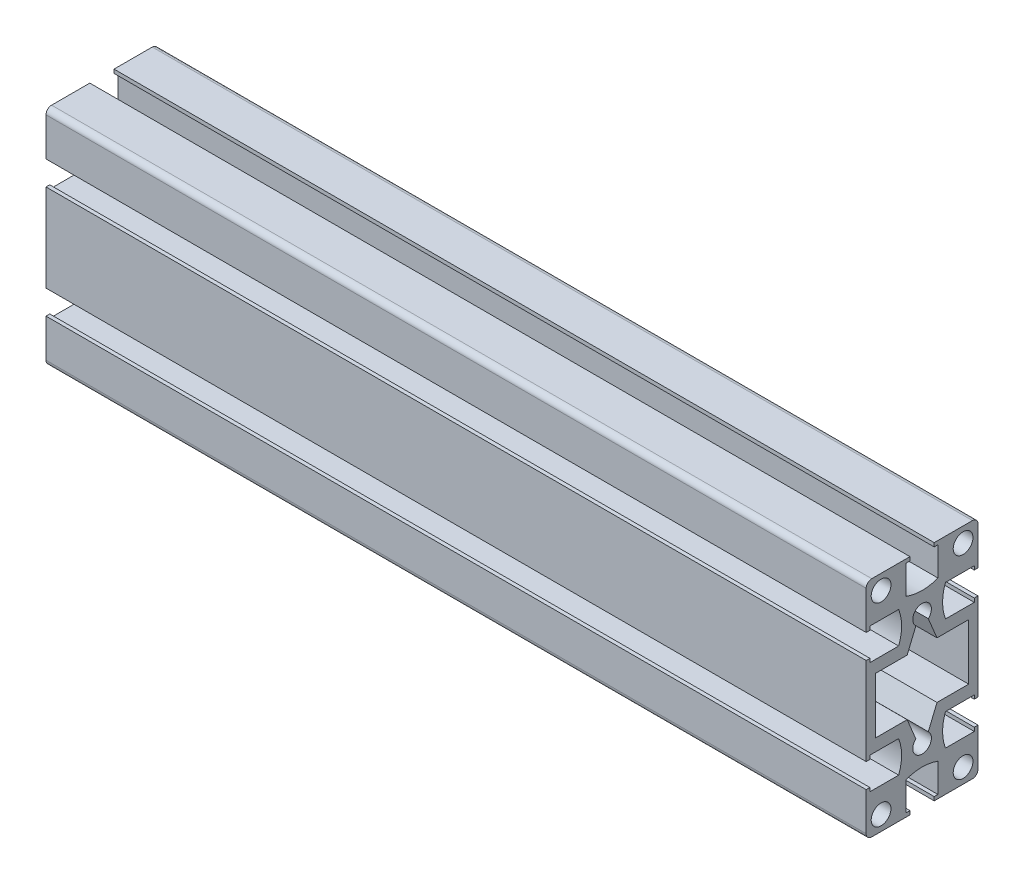
SolidWorks part; units mm, degrees
ref_plane "前视基准面" through (0, 0, 0) normal (0, 0, 1) x (1, 0, 0)
ref_plane "上视基准面" through (0, 0, 0) normal (0, 1, 0) x (1, 0, 0)
ref_plane "右视基准面" through (0, 0, 0) normal (1, 0, 0) x (0, 0, -1)
sketch "草图1" plane through (0, 0, 0) normal (0, 1, 0) x (1, 0, 0)
  line L0 (0, 0) -> (220, 0)
  dimension "D1" = 220
other "铝型材 30 X 60G X R1.5(1)"
ref_plane "基准面1" through (0, 0, 0) normal (1, 0, 0) x (0, 0, -1)
sketch "Sketch1" plane through (0, 0, 0) normal (1, 0, 0) x (0, 0, -1)
  line L0 (-3.25, 30) -> (-3.25, 29)
  line L1 (-13.5, 30) -> (-3.25, 30)
  line L2 (-15, 28.5) -> (-15, 18.25)
  line L3 (-13.5, -30) -> (-3.25, -30)
  line L4 (15, 28.5) -> (15, 18.25)
  line L5 (-12.5, 7.5) -> (-4, 7.5)
  line L6 (-12.5, 7.5) -> (-12.5, -7.5)
  line L7 (-12.5, -7.5) -> (-4, -7.5)
  line L8 (0, 30) -> (0, 0) construction
  line L9 (0, 0) -> (15, 0) construction
  line L10 (12.5, 7.5) -> (12.5, -7.5)
  line L11 (-3.25, 29) -> (-4.25, 29)
  line L12 (-4.25, 29) -> (-4.25, 21.2778)
  line L13 (-11, 26) -> (-15, 30) construction
  line L14 (4.25, 29) -> (4.25, 21.2778)
  line L15 (3.25, 29) -> (4.25, 29)
  line L16 (3.25, 30) -> (3.25, 29)
  line L17 (3.25, 30) -> (13.5, 30)
  line L18 (-1.6656, 13.1357) -> (-4, 7.5)
  line L19 (1.6656, 13.1357) -> (4, 7.5)
  line L20 (4, 7.5) -> (12.5, 7.5)
  line L21 (1.6656, -13.1357) -> (4, -7.5)
  line L22 (-1.6656, -13.1357) -> (-4, -7.5)
  line L23 (4, -7.5) -> (12.5, -7.5)
  line L24 (15, 18.25) -> (14, 18.25)
  line L25 (14, 18.25) -> (14, 19.25)
  line L26 (14, 19.25) -> (6.2778, 19.25)
  line L27 (14, 10.75) -> (6.2778, 10.75)
  line L28 (14, 11.75) -> (14, 10.75)
  line L29 (15, 11.75) -> (14, 11.75)
  line L30 (3.25, 0) -> (3.25, 1) [skipped]
  line L31 (3.25, 1) -> (4.25, 1) [skipped]
  line L32 (4.25, 1) -> (4.25, 8.7222) [skipped]
  line L33 (-4.25, 1) -> (-4.25, 8.7222) [skipped]
  line L34 (-3.25, 1) -> (-4.25, 1) [skipped]
  line L35 (-3.25, 0) -> (-3.25, 1) [skipped]
  line L36 (-15, 11.75) -> (-14, 11.75)
  line L37 (-14, 11.75) -> (-14, 10.75)
  line L38 (-14, 10.75) -> (-6.2778, 10.75)
  line L39 (-14, 19.25) -> (-6.2778, 19.25)
  line L40 (-14, 18.25) -> (-14, 19.25)
  line L41 (-15, 18.25) -> (-14, 18.25)
  line L42 (-15, 11.75) -> (-15, -11.75)
  line L43 (15, 11.75) -> (15, -11.75)
  line L44 (-15, -18.25) -> (-14, -18.25)
  line L45 (-14, -18.25) -> (-14, -19.25)
  line L46 (-14, -19.25) -> (-6.2778, -19.25)
  line L47 (-14, -10.75) -> (-6.2778, -10.75)
  line L48 (-14, -11.75) -> (-14, -10.75)
  line L49 (-15, -11.75) -> (-14, -11.75)
  line L50 (15, -11.75) -> (14, -11.75)
  line L51 (14, -11.75) -> (14, -10.75)
  line L52 (14, -10.75) -> (6.2778, -10.75)
  line L53 (14, -19.25) -> (6.2778, -19.25)
  line L54 (14, -18.25) -> (14, -19.25)
  line L55 (15, -18.25) -> (14, -18.25)
  line L56 (3.25, -30) -> (3.25, -29)
  line L57 (3.25, -29) -> (4.25, -29)
  line L58 (4.25, -29) -> (4.25, -21.2778)
  line L59 (-4.25, -29) -> (-4.25, -21.2778)
  line L60 (-3.25, -29) -> (-4.25, -29)
  line L61 (-3.25, -30) -> (-3.25, -29)
  line L62 (3.25, -30) -> (13.5, -30)
  line L63 (-15, -18.25) -> (-15, -28.5)
  line L64 (15, -18.25) -> (15, -28.5)
  arc A0 (-4.25, 21.2778) -> (4.25, 21.2778) centre (0, 32.5) ccw
  circle A1 centre (-11, 26) radius 2.65
  circle A2 centre (11, 26) radius 2.65
  arc A3 (-15, 28.5) -> (-13.5, 30) centre (-13.5, 28.5) cw
  arc A4 (15, 28.5) -> (13.5, 30) centre (13.5, 28.5) ccw
  arc A5 (15, -28.5) -> (13.5, -30) centre (13.5, -28.5) cw
  arc A6 (-13.5, -30) -> (-15, -28.5) centre (-13.5, -28.5) cw
  arc A7 (1.6656, 13.1357) -> (-1.6656, 13.1357) centre (0, 15) ccw
  arc A8 (-1.6656, -13.1357) -> (1.6656, -13.1357) centre (0, -15) ccw
  arc A9 (6.2778, 19.25) -> (6.2778, 10.75) centre (17.5, 15) ccw
  arc A10 (4.25, 8.7222) -> (-4.25, 8.7222) centre (0, -2.5) ccw [skipped]
  arc A11 (-6.2778, 10.75) -> (-6.2778, 19.25) centre (-17.5, 15) ccw
  arc A12 (-6.2778, -10.75) -> (-6.2778, -19.25) centre (-17.5, -15) cw
  arc A13 (6.2778, -19.25) -> (6.2778, -10.75) centre (17.5, -15) cw
  circle A14 centre (11, -26) radius 2.65
  arc A15 (-4.25, -21.2778) -> (4.25, -21.2778) centre (0, -32.5) cw
  circle A16 centre (-11, -26) radius 2.65
  point P102 (15, -30)
  point P103 (-15, -30)
  point P104 (0, 0)
  dimension "D1" = 60
  dimension "D2" = 30
  dimension "D3" = 15
  dimension "D4" = 2.5
  dimension "D5" = 6.5
  dimension "D6" = 8.5
  dimension "D7" = 12
  dimension "D8" = 1
  dimension "D10" = 5.3
  dimension "D11" = 4
  dimension "D12" = 1.5
  dimension "D13" = 5
  dimension "D14" = 30
  dimension "D9" = 9.5
  dimension "D15" = 45
  dimension "D16" = 8
